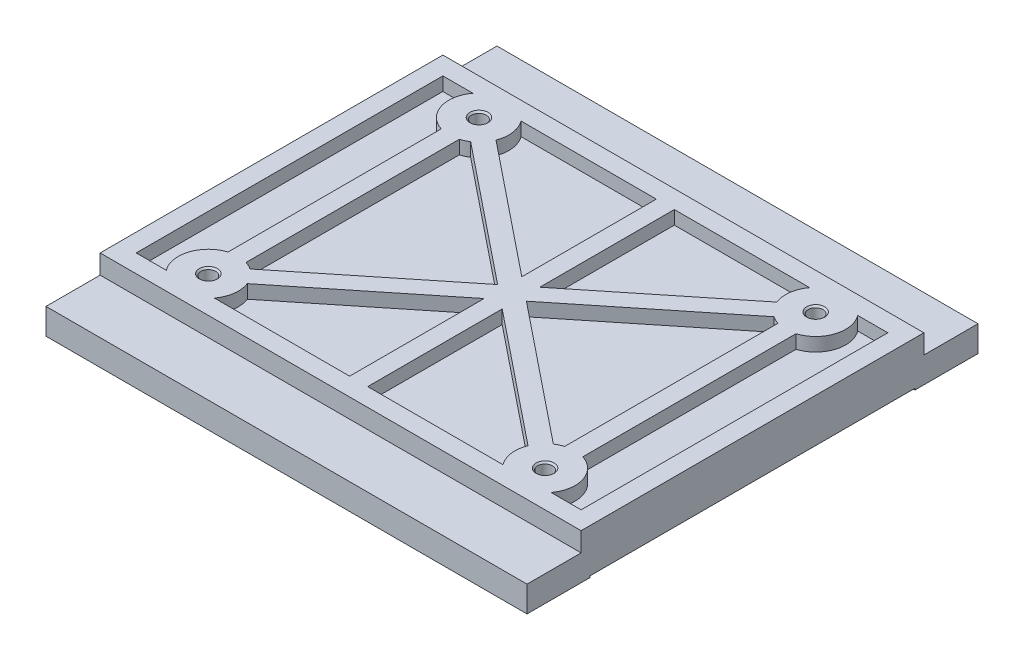
SolidWorks part; units mm, degrees
ref_plane "Front Plane" through (0, 0, 0) normal (0, 0, 1) x (1, 0, 0)
ref_plane "Top Plane" through (0, 0, 0) normal (0, 1, 0) x (1, 0, 0)
ref_plane "Right Plane" through (0, 0, 0) normal (1, 0, 0) x (0, 0, -1)
ref_plane "Plane1" through (0, 0, 0) normal (1, 0, 0) x (0, 0, -1)
sketch "Sketch1" plane through (0, 0, 0) normal (1, 0, 0) x (0, 0, -1)
  line L0 (-37.5, 4.5) -> (-27, 4.5)
  line L1 (-27, 4.5) -> (-27, 4.75)
  line L2 (-27, 4.75) -> (27, 4.75)
  line L3 (27, 4.75) -> (27, 4.5)
  line L4 (27, 4.5) -> (37.5, 4.5)
  line L5 (37.5, 4.5) -> (37.5, 8.8)
  line L6 (37.5, 8.8) -> (28.5, 8.8)
  line L7 (28.5, 8.8) -> (28.5, 9.75)
  line L8 (28.5, 9.75) -> (-28.5, 9.75)
  line L9 (-28.5, 9.75) -> (-28.5, 8.8)
  line L10 (-28.5, 8.8) -> (-37.5, 8.8)
  line L11 (-37.5, 8.8) -> (-37.5, 4.5)
extrude "Boss-Extrude1" add sketch "Sketch1" along normal blind 80
ref_plane "Plane2" through (0, 9.75, 0) normal (0, 1, 0) x (1, 0, 0)
sketch "Sketch2" plane through (0, 9.75, 0) normal (0, 1, 0) x (1, 0, 0)
  line L0 (0, 28.5) -> (0, -28.5)
  line L1 (0, -28.5) -> (80, -28.5)
  line L2 (80, -28.5) -> (80, 28.5)
  line L3 (80, 28.5) -> (0, 28.5)
  line L4 (69.5, 17.7303) -> (69.5, -17.7303)
  line L5 (72, -25.5) -> (77, -25.5)
  line L6 (77, -25.5) -> (77, 25.5)
  line L7 (77, 25.5) -> (72, 25.5)
  line L8 (42.3947, 0) -> (65.2216, -18.343)
  line L9 (66.5, -17.7303) -> (66.5, 17.7303)
  line L10 (65.2216, 18.343) -> (42.3947, 0)
  line L11 (41.5, 25.5) -> (41.5, 3.1296)
  line L12 (41.5, 3.1296) -> (63.3424, 20.6816)
  line L13 (64, 25.5) -> (41.5, 25.5)
  line L14 (41.5, -25.5) -> (64, -25.5)
  line L15 (63.3424, -20.6816) -> (41.5, -3.1296)
  line L16 (41.5, -3.1296) -> (41.5, -25.5)
  line L17 (16.6576, 20.6816) -> (38.5, 3.1296)
  line L18 (38.5, 3.1296) -> (38.5, 25.5)
  line L19 (38.5, 25.5) -> (16, 25.5)
  line L20 (16, -25.5) -> (38.5, -25.5)
  line L21 (38.5, -25.5) -> (38.5, -3.1296)
  line L22 (38.5, -3.1296) -> (16.6576, -20.6816)
  line L23 (14.7784, -18.343) -> (37.6053, 0)
  line L24 (37.6053, 0) -> (14.7784, 18.343)
  line L25 (13.5, 17.7303) -> (13.5, -17.7303)
  line L26 (3, -25.5) -> (8, -25.5)
  line L27 (10.5, -17.7303) -> (10.5, 17.7303)
  line L28 (8, 25.5) -> (3, 25.5)
  line L29 (3, 25.5) -> (3, -25.5)
  arc A0 (69.5, -17.7303) -> (72, -25.5) centre (68, -22.5) cw
  arc A1 (72, 25.5) -> (69.5, 17.7303) centre (68, 22.5) cw
  arc A2 (65.2216, -18.343) -> (66.5, -17.7303) centre (68, -22.5) cw
  arc A3 (66.5, 17.7303) -> (65.2216, 18.343) centre (68, 22.5) cw
  arc A4 (63.3424, 20.6816) -> (64, 25.5) centre (68, 22.5) cw
  arc A5 (64, -25.5) -> (63.3424, -20.6816) centre (68, -22.5) cw
  arc A6 (16, 25.5) -> (16.6576, 20.6816) centre (12, 22.5) cw
  arc A7 (16.6576, -20.6816) -> (16, -25.5) centre (12, -22.5) cw
  arc A8 (13.5, -17.7303) -> (14.7784, -18.343) centre (12, -22.5) cw
  arc A9 (14.7784, 18.343) -> (13.5, 17.7303) centre (12, 22.5) cw
  arc A10 (8, -25.5) -> (10.5, -17.7303) centre (12, -22.5) cw
  arc A11 (10.5, 17.7303) -> (8, 25.5) centre (12, 22.5) cw
extrude "Boss-Extrude2" add sketch "Sketch2" along normal blind 2.25
ref_plane "Plane3" through (0, 0, 22.5) normal (0, 0, 1) x (1, 0, 0)
sketch "Sketch3" plane through (0, 0, 22.5) normal (0, 0, 1) x (1, 0, 0)
  line L0 (12, 12) -> (13.5, 12)
  line L1 (13.5, 12) -> (13.2295, 11.7295)
  line L2 (13.2295, 11.7295) -> (13.2295, 5.0205)
  line L3 (13.2295, 5.0205) -> (13.5, 4.75)
  line L4 (13.5, 4.75) -> (12, 4.75)
  line L5 (12, 4.75) -> (12, 12)
  line L6 (12, 4.75) -> (12, 12) construction
revolve "Cut-Revolve1" cut sketch "Sketch3" angle 360 about L6
ref_plane "Plane4" through (0, 0, 22.5) normal (0, 0, 1) x (1, 0, 0)
sketch "Sketch4" plane through (0, 0, 22.5) normal (0, 0, 1) x (1, 0, 0)
  line L0 (68, 12) -> (69.5, 12)
  line L1 (69.5, 12) -> (69.2295, 11.7295)
  line L2 (69.2295, 11.7295) -> (69.2295, 5.0205)
  line L3 (69.2295, 5.0205) -> (69.5, 4.75)
  line L4 (69.5, 4.75) -> (68, 4.75)
  line L5 (68, 4.75) -> (68, 12)
  line L6 (68, 4.75) -> (68, 12) construction
revolve "Cut-Revolve2" cut sketch "Sketch4" angle 360 about L6
ref_plane "Plane5" through (0, 0, -22.5) normal (0, 0, 1) x (1, 0, 0)
sketch "Sketch5" plane through (0, 0, -22.5) normal (0, 0, 1) x (1, 0, 0)
  line L0 (12, 12) -> (13.5, 12)
  line L1 (13.5, 12) -> (13.2295, 11.7295)
  line L2 (13.2295, 11.7295) -> (13.2295, 5.0205)
  line L3 (13.2295, 5.0205) -> (13.5, 4.75)
  line L4 (13.5, 4.75) -> (12, 4.75)
  line L5 (12, 4.75) -> (12, 12)
  line L6 (12, 4.75) -> (12, 12) construction
revolve "Cut-Revolve3" cut sketch "Sketch5" angle 360 about L6
ref_plane "Plane6" through (0, 0, -22.5) normal (0, 0, 1) x (1, 0, 0)
sketch "Sketch6" plane through (0, 0, -22.5) normal (0, 0, 1) x (1, 0, 0)
  line L0 (68, 12) -> (69.5, 12)
  line L1 (69.5, 12) -> (69.2295, 11.7295)
  line L2 (69.2295, 11.7295) -> (69.2295, 5.0205)
  line L3 (69.2295, 5.0205) -> (69.5, 4.75)
  line L4 (69.5, 4.75) -> (68, 4.75)
  line L5 (68, 4.75) -> (68, 12)
  line L6 (68, 4.75) -> (68, 12) construction
revolve "Cut-Revolve4" cut sketch "Sketch6" angle 360 about L6
ref_plane "Plane7" through (40, 0, 0) normal (1, 0, 0) x (0, 0, -1)
